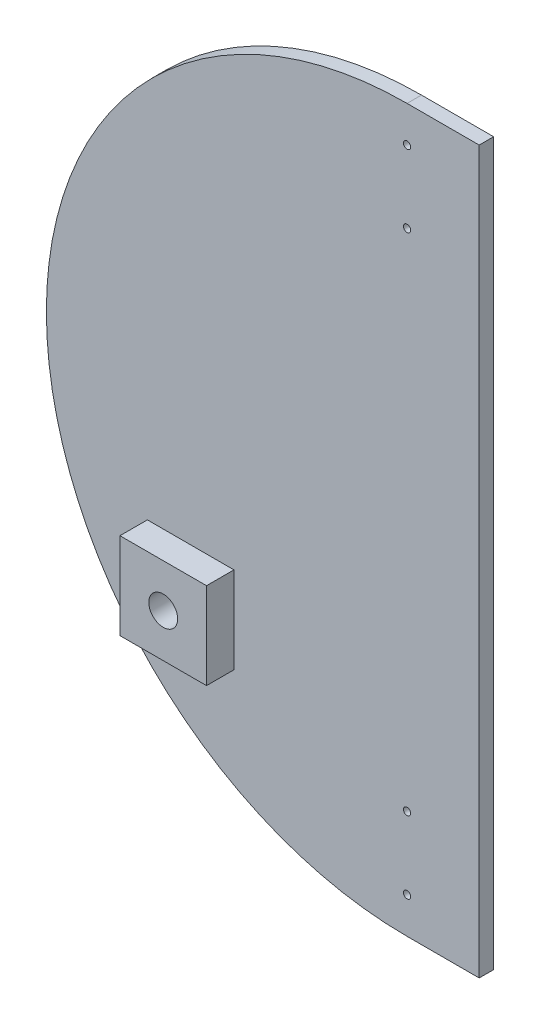
SolidWorks part; units mm, degrees
ref_plane "前视基准面" through (0, 0, 0) normal (0, 0, 1) x (1, 0, 0)
ref_plane "上视基准面" through (0, 0, 0) normal (0, 1, 0) x (1, 0, 0)
ref_plane "右视基准面" through (0, 0, 0) normal (1, 0, 0) x (0, 0, -1)
other "Configuration Table"
sketch "草图1" plane through (0, 0, 0) normal (0, 0, 1) x (1, 0, 0)
  line L0 (-1000, 0) -> (49000, 0) construction
  line L1 (0, 125) -> (25, 125)
  line L3 (25, -125) -> (0, -125)
  line L4 (25, 125) -> (25, -125)
  arc A0 (0, 125) -> (0, -125) centre (0, 0) ccw
  circle A1 centre (0, 100) radius 12.5 construction
  circle A2 centre (0, 112.5) radius 1.25
  circle A3 centre (0, 87.5) radius 1.25
  circle A4 centre (0, -100) radius 12.5 construction
  circle A5 centre (0, -87.5) radius 1.25
  circle A6 centre (0, -112.5) radius 1.25
  circle A7 centre (-75, -60) radius 5
  dimension "D2" = 25
  dimension "D3" = 250
  dimension "D4" = 2.5
  dimension "D5" = 2.5
  dimension "D9" = 10
  dimension "D1" = 100
  dimension "D6" = 25
  dimension "D7" = 75
  dimension "D8" = 40
extrude "凸台-拉伸1" add sketch "草图1" along normal blind 5
sketch "草图2" plane through (0, 0, 5) normal (0, 0, 1) x (1, 0, 0)
  line L1 (-90, -75) -> (-60, -75)
  line L2 (-90, -75) -> (-90, -45)
  line L3 (-90, -45) -> (-60, -45)
  line L4 (-60, -75) -> (-60, -45)
  line L5 (-90, -75) -> (-60, -45) construction
  line L6 (-90, -45) -> (-60, -75) construction
  point P0 (-75, -60)
  dimension "D1" = 30
  dimension "D2" = 30
extrude "凸台-拉伸2" add sketch "草图2" along normal blind 9.5
sketch "草图3" plane through (0, 0, 5) normal (0, 0, -1) x (-1, 0, 0)
  circle A1 centre (75, -60) radius 5
  circle A2 centre (75, -60) radius 5
  dimension "D1" = 0
extrude "切除-拉伸1" cut sketch "草图3" against normal blind 9.5
